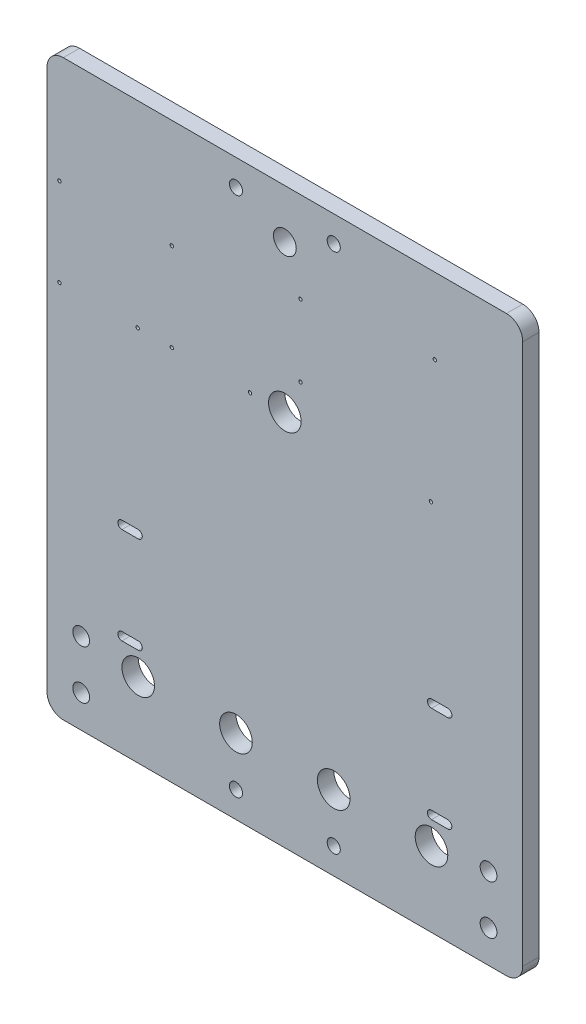
SolidWorks part; units mm, degrees
material "Pine"
ref_plane "Front Plane" through (0, 0, 0) normal (0, 0, 1) x (1, 0, 0)
ref_plane "Top Plane" through (0, 0, 0) normal (0, 1, 0) x (1, 0, 0)
ref_plane "Right Plane" through (0, 0, 0) normal (1, 0, 0) x (0, 0, -1)
ref_plane "Plane1" through (0, 0, 6.35) normal (0, 0, 1) x (1, 0, 0)
sketch "Sketch2" plane through (0, 0, 6.35) normal (0, 0, 1) x (1, 0, 0)
  line L0 (-92.71, -111.76) -> (92.71, -111.76) construction
  line L1 (92.71, -111.76) -> (-92.71, -111.76)
  line L2 (92.71, -111.76) -> (92.71, 111.76)
  line L3 (92.71, 111.76) -> (-92.71, 111.76)
  line L4 (-92.71, -111.76) -> (-92.71, 111.76)
  line L5 (92.71, -111.76) -> (-92.71, 111.76) construction
  line L6 (92.71, 111.76) -> (-92.71, -111.76) construction
  line L7 (72.39, -91.44) -> (92.71, -111.76) construction
  circle A0 centre (-19.05, 101.6) radius 2.5527
  circle A1 centre (19.05, 101.6) radius 2.5527
  circle A3 centre (-19.05, -101.6) radius 2.5527
  circle A4 centre (19.05, -101.6) radius 2.5527
  point P0 (0, 0)
  dimension "D1" = 5.1054
extrude "Boss-Extrude1" add sketch "Sketch2" along normal blind 6.35
fillet "Fillet2" radius 6.35 4 edges at (-92.71, -111.76, 9.525) (92.71, -111.76, 9.525) (92.71, 111.76, 9.525) (-92.71, 111.76, 9.525)
sketch "Sketch5" plane through (0, 0, 12.7) normal (0, 0, 1) x (1, 0, 0)
  line L0 (86.36, 111.76) -> (-86.36, 111.76) construction
  circle A0 centre (0, 92.71) radius 19.05
  circle A1 centre (0, 92.71) radius 4.445
  dimension "D1" = 38.1
  dimension "D2" = 8.89
extrude "Cut-Extrude3" cut sketch "Sketch5" against normal through all contours A1
sketch "Sketch6" plane through (0, 0, 6.35) normal (0, 0, -1) x (-1, 0, 0)
  line L0 (0, -111.76) -> (0, 0) construction
  line L1 (86.36, -111.76) -> (-86.36, -111.76) construction
  circle A0 centre (-79.375, -80.01) radius 3.2639
  circle A1 centre (79.375, -80.01) radius 3.2639
  circle A2 centre (-79.375, -99.06) radius 3.2639
  circle A3 centre (79.375, -99.06) radius 3.2639
  dimension "D1" = 6.5278
  dimension "D2" = 80.01
  dimension "D3" = 79.375
  dimension "D4" = 19.05
extrude "Cut-Extrude6" cut sketch "Sketch6" against normal through all
sketch "Sketch7" plane through (0, 0, 12.7) normal (0, 0, 1) x (1, 0, 0)
  line L1 (82.55, -101.6) -> (-82.55, -101.6)
  line L2 (82.55, -101.6) -> (82.55, 101.6)
  line L3 (82.55, 101.6) -> (-82.55, 101.6)
  line L4 (-82.55, -101.6) -> (-82.55, 101.6)
  line L5 (82.55, -101.6) -> (-82.55, 101.6) construction
  line L6 (82.55, 101.6) -> (-82.55, -101.6) construction
  point P0 (0, 0)
  dimension "D1" = 165.1
  dimension "D2" = 203.2
sketch "Sketch8" plane through (0, 0, 12.7) normal (0, 0, 1) x (1, 0, 0)
  line L0 (-2.159, 28.956) -> (2.159, 28.956) construction
  line L1 (63.5, -34.4805) -> (57.15, -34.4805) construction
  line L2 (63.5, -36.068) -> (57.15, -36.068)
  line L3 (63.5, -32.893) -> (57.15, -32.893)
  line L4 (-57.15, -34.4805) -> (-63.5, -34.4805) construction
  line L5 (-57.15, -36.068) -> (-63.5, -36.068)
  line L6 (-57.15, -32.893) -> (-63.5, -32.893)
  line L7 (-57.15, -72.0725) -> (-63.5, -72.0725) construction
  line L8 (-57.15, -73.66) -> (-63.5, -73.66)
  line L9 (-57.15, -70.485) -> (-63.5, -70.485)
  line L10 (57.15, -72.0725) -> (63.5, -72.0725) construction
  line L11 (57.15, -70.485) -> (63.5, -70.485)
  line L12 (57.15, -73.66) -> (63.5, -73.66)
  line L13 (87.63, -70.485) -> (-87.63, -70.485) construction
  line L14 (-87.63, -36.068) -> (87.63, -36.068) construction
  line L15 (-88.9, -69.215) -> (-88.9, -37.338) construction
  line L16 (88.9, -37.338) -> (88.9, -69.215) construction
  line L18 (-86.36, -111.76) -> (86.36, -111.76) construction
  circle A0 centre (0, 35.306) radius 6.35
  arc A1 (63.5, -36.068) -> (63.5, -32.893) centre (63.5, -34.4805) ccw
  arc A2 (57.15, -32.893) -> (57.15, -36.068) centre (57.15, -34.4805) ccw
  arc A3 (-57.15, -36.068) -> (-57.15, -32.893) centre (-57.15, -34.4805) ccw
  arc A4 (-63.5, -32.893) -> (-63.5, -36.068) centre (-63.5, -34.4805) ccw
  arc A5 (-57.15, -73.66) -> (-57.15, -70.485) centre (-57.15, -72.0725) ccw
  arc A6 (-63.5, -70.485) -> (-63.5, -73.66) centre (-63.5, -72.0725) ccw
  arc A7 (57.15, -70.485) -> (57.15, -73.66) centre (57.15, -72.0725) ccw
  arc A8 (63.5, -73.66) -> (63.5, -70.485) centre (63.5, -72.0725) ccw
  circle A9 centre (57.15, -82.55) radius 6.35
  circle A10 centre (19.05, -82.55) radius 6.35
  circle A11 centre (-19.05, -82.55) radius 6.35
  circle A12 centre (-57.15, -82.55) radius 6.35
  point P0 (58.43, 82.2082)
  point P1 (6.08, 76.5082)
  point P3 (6.08, 48.5082)
  point P5 (56.93, 33.5082)
  point P7 (-44.0436, 35.069)
  point P9 (-13.5636, 35.069)
  point P11 (-44.0436, 69.4098)
  point P13 (-57.3786, 35.069)
  point P15 (-87.8586, 35.069)
  point P17 (-87.8586, 69.4098)
  point P27 (60.325, -34.4805)
  point P32 (-60.325, -34.4805)
  point P39 (-60.325, -72.0725)
  point P46 (60.325, -72.0725)
  point P70 (0, -111.76)
  dimension "D1" = 12.7
  dimension "D2" = 25.4
  dimension "D4" = 25.4
  dimension "D6" = 57.15
  dimension "D8" = 82.55
  dimension "D9" = 38.1
  dimension "D3" = 6.35
  dimension "D5" = 3.175
  dimension "D7" = 4
extrude "Cut-Extrude7" cut sketch "Sketch8" against normal through all
hole_wizard "#55 (0.052) Diameter Hole1" positions "Sketch10" profile "Sketch9" hole size "#55" standard "ANSI Inch" end condition through all
sketch "Sketch10" plane through (0, 0, 12.7) normal (0, 0, 1) x (1, 0, 0)
  point P0 (-13.5636, 35.069)
  point P3 (-44.0436, 35.069)
  point P6 (-57.3786, 35.069)
  point P9 (-44.0436, 69.4098)
  point P12 (-87.8586, 35.069)
  point P15 (-87.8586, 69.4098)
sketch "Sketch9" plane through (-13.5636, 35.069, 12.7) normal (1, 0, 0) x (0, -1, 0)
  line L0 (0, 0) -> (0, 6.35)
  line L1 (0, 6.35) -> (0.6604, 6.35)
  line L2 (0.6604, 6.35) -> (0.6604, 0)
  line L5 (0.6604, 0) -> (0, 0)
  line L11 (0, -6.35) -> (0, 107.95) construction
  dimension "Thru Hole Dia." = 1.3208
  dimension "Thru Hole Depth" = 6.35
hole_wizard "#55 (0.052) Diameter Hole2" positions "Sketch12" profile "Sketch11" hole size "#55" standard "ANSI Inch"
sketch "Sketch12" plane through (0, 0, 12.7) normal (0, 0, 1) x (1, 0, 0)
  point P0 (6.08, 48.5082)
  point P3 (6.08, 76.5082)
  point P6 (58.43, 82.2082)
  point P9 (56.93, 33.5082)
sketch "Sketch11" plane through (6.08, 48.5082, 12.7) normal (1, 0, 0) x (0, -1, 0)
  line L0 (0, 0) -> (0, 25.7968)
  line L1 (0, 25.7968) -> (0.6604, 25.4)
  line L2 (0.6604, 25.4) -> (0.6604, 0)
  line L5 (0.6604, 0) -> (0, 0)
  line L10 (0, 25.7968) -> (-0.6604, 25.4) construction
  line L11 (0, -6.35) -> (0, 107.95) construction
  dimension "Hole Dia." = 1.3208
  dimension "Hole Depth" = 25.4
  dimension "Drill Angle" = 118
